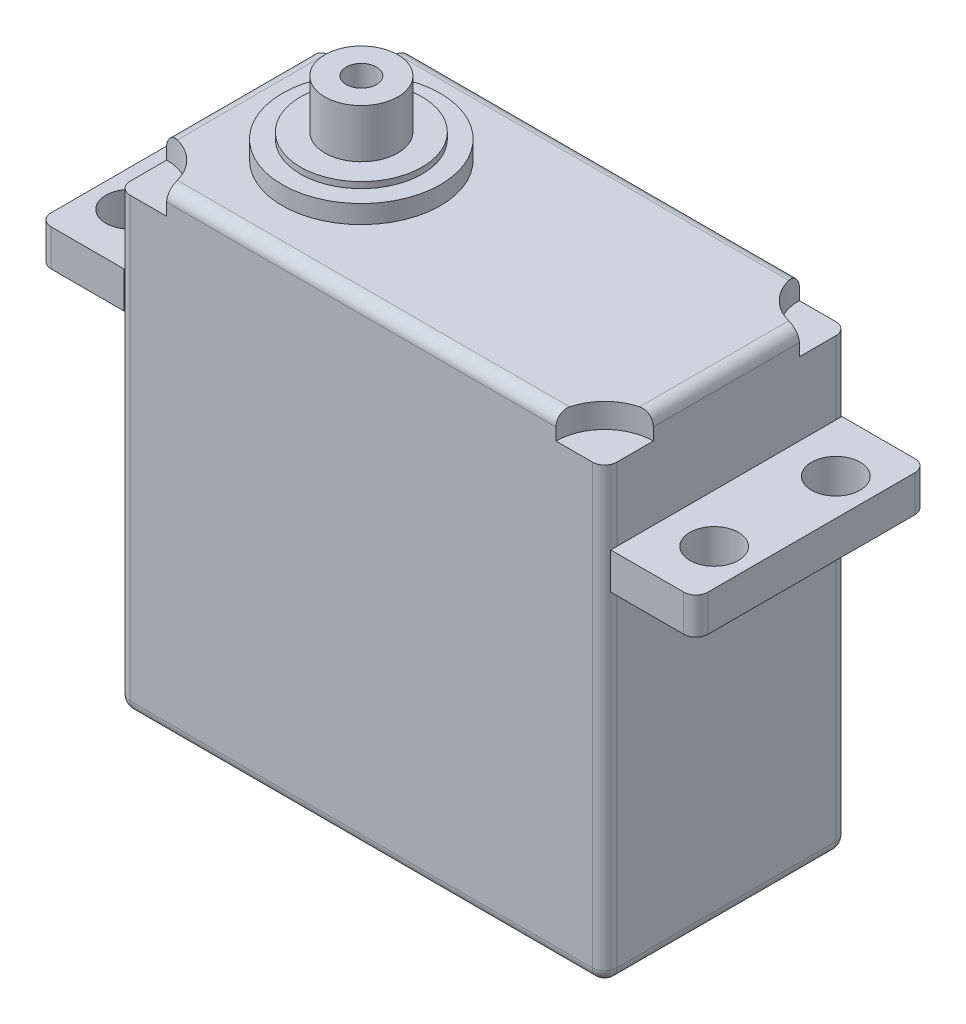
SolidWorks part; units mm, degrees
ref_plane "Front Plane" through (0, 0, 0) normal (0, 0, 1) x (1, 0, 0)
ref_plane "Top Plane" through (0, 0, 0) normal (0, 1, 0) x (1, 0, 0)
ref_plane "Right Plane" through (0, 0, 0) normal (1, 0, 0) x (0, 0, -1)
sketch "草图2" plane through (0, 0, 0) normal (0, 0, 1) x (1, 0, 0)
  line L1 (0, 0) -> (40, 0)
  line L2 (0, 0) -> (0, -39)
  line L3 (0, -39) -> (40, -39)
  line L4 (40, 0) -> (40, -39)
  dimension "D1" = 40
  dimension "D2" = 39
extrude "凸台-拉伸1" add sketch "草图2" along normal mid plane 20
ref_plane "基准面1" through (0, -20, 0) normal (0, 1, 0) x (1, 0, 0)
fillet "圆角1" radius 1 12 edges at (20, -39, 10) (40, 0, 0) (0, 0, 0) (40, -19.5, -10) (20, 0, -10) (0, -19.5, -10) (20, -39, -10) (40, -39, 0) (40, -19.5, 10) (20, 0, 10) (0, -19.5, 10) (0, -39, 0)
sketch "草图6" plane through (0, 0, 0) normal (0, -1, 0) x (1, 0, 0)
  line L0 (0, -9) -> (0, 9) construction
  line L1 (1, 10) -> (39, 10) construction
  line L2 (20, -10) -> (20, 10) construction
  line L3 (39, -10) -> (1, -10) construction
  line L4 (0, 0) -> (40, 0) construction
  line L5 (40, 9) -> (40, -9) construction
  circle A0 centre (0, 10) radius 4
  circle A1 centre (40, 10) radius 4
  circle A2 centre (40, -10) radius 4
  circle A3 centre (0, -10) radius 4
  dimension "D1" = 8
extrude "切除-拉伸1" cut sketch "草图6" along normal blind 2
hole_wizard "Ø2.0 (2) 直径孔2" positions "草图15" profile "草图14" hole size "Ø2.0" standard "GB"
sketch "草图15" plane through (0, -39, 0) normal (0, -1, 0) x (-1, 0, 0)
  line L0 (-2.5, 7.5) -> (-37.5, 7.5) construction
  line L1 (-37.5, 7.5) -> (-37.5, -7.5) construction
  line L2 (-37.5, -7.5) -> (-20, -7.5) construction
  line L4 (0, 0) -> (-40, 0) construction
  line L5 (-40, -9) -> (-40, 9) construction
  line L7 (-20, 7.5) -> (-20, -7.5) construction
  line L8 (-20, -7.5) -> (-2.5, -7.5) construction
  line L9 (-20, 10) -> (-20, -10) construction
  line L10 (-39, 10) -> (-1, 10) construction
  line L11 (-1, -10) -> (-39, -10) construction
  point P6 (-37.5, 7.5)
  point P8 (-37.5, -7.5)
  point P13 (-2.5, 7.5)
  point P33 (-2.5, -7.5)
  dimension "D1" = 15
  dimension "D2" = 35
sketch "草图14" plane through (37.5, -39, -7.5) normal (1, 0, 0) x (0, 0, -1)
  line L0 (0, 0) -> (0, 10.6009)
  line L1 (0, 10.6009) -> (1, 10)
  line L2 (1, 10) -> (1, 0)
  line L5 (1, 0) -> (0, 0)
  line L10 (0, 10.6009) -> (-1, 10) construction
  line L11 (0, -6.35) -> (0, 107.95) construction
  dimension "孔直径" = 2
  dimension "孔深度" = 10
  dimension "导头角度" = 118
sketch "草图16" plane through (0, 0, 0) normal (0, 1, 0) x (1, 0, 0)
  line L0 (40, 0) -> (0, 0) construction
  line L1 (40, 6) -> (40, -6) construction
  line L3 (0, -9.5) -> (-7, -9.5)
  line L4 (0, -9.5) -> (0, 9.5)
  line L5 (0, 9.5) -> (-7, 9.5)
  line L6 (-7, -9.5) -> (-7, 9.5)
  line L7 (0, -6) -> (0, 6) construction
  line L8 (20, -10) -> (20, 10) construction
  line L9 (36, -10) -> (4, -10) construction
  line L10 (4, 10) -> (36, 10) construction
  line L11 (47, -9.5) -> (47, 9.5)
  line L12 (40, 9.5) -> (47, 9.5)
  line L13 (40, -9.5) -> (40, 9.5)
  line L14 (40, -9.5) -> (47, -9.5)
  circle A0 centre (-4, -5) radius 2
  circle A1 centre (-4, 5) radius 2
  circle A2 centre (44, 5) radius 2
  circle A3 centre (44, -5) radius 2
  dimension "D3" = 4
  dimension "D4" = 10
  dimension "D1" = 7
  dimension "D2" = 19
  dimension "D5" = 48
extrude "凸台-拉伸2" add sketch "草图16" against normal blind 3 from offset 8 offset against normal yes
sketch "草图17" plane through (0, 0, 0) normal (0, 1, 0) x (1, 0, 0)
  line L0 (0, 0) -> (40, 0) construction
  line L1 (40, 9) -> (40, -9) construction
  circle A0 centre (10, 0) radius 6.5
  dimension "D1" = 13
  dimension "D2" = 30
extrude "凸台-拉伸3" add sketch "草图17" along normal blind 1.5
sketch "草图18" plane through (0, 1.5, 0) normal (0, 1, 0) x (1, 0, 0)
  circle A0 centre (10, 0) radius 5
  dimension "D1" = 10
extrude "凸台-拉伸4" add sketch "草图18" along normal blind 0.5
sketch "草图19" plane through (0, 2, 0) normal (0, 1, 0) x (1, 0, 0)
  circle A0 centre (10, 0) radius 3
  dimension "D1" = 6
extrude "凸台-拉伸5" add sketch "草图19" along normal blind 4
fillet "圆角2" radius 1 4 edges at (-7, -9.5, -9.5) (-7, -9.5, 9.5) (47, -9.5, 9.5) (47, -9.5, -9.5)
hole_wizard "M3 螺纹孔1" positions "草图21" profile "草图20" tap size "M3" standard "GB"
sketch "草图21" plane through (0, 6, 0) normal (0, 1, 0) x (1, 0, 0)
  point P0 (10, 0)
cosmetic thread "孔螺蚊线1" parameters "D1"=3.05, "D2"=3
sketch "草图20" plane through (10, 6, 0) normal (1, 0, 0) x (0, 0, 1)
  line L0 (0, 0) -> (0, 6.3011)
  line L1 (0, 6.3011) -> (1.25, 5.55)
  line L2 (1.25, 5.55) -> (1.25, 0)
  line L5 (1.25, 0) -> (0, 0)
  line L10 (0, 6.3011) -> (-1.25, 5.55) construction
  line L11 (0, -6.35) -> (0, 107.95) construction
  dimension "螺纹孔钻头直径" = 2.5
  dimension "螺纹孔钻头深度" = 5.55
  dimension "导头角度" = 118
